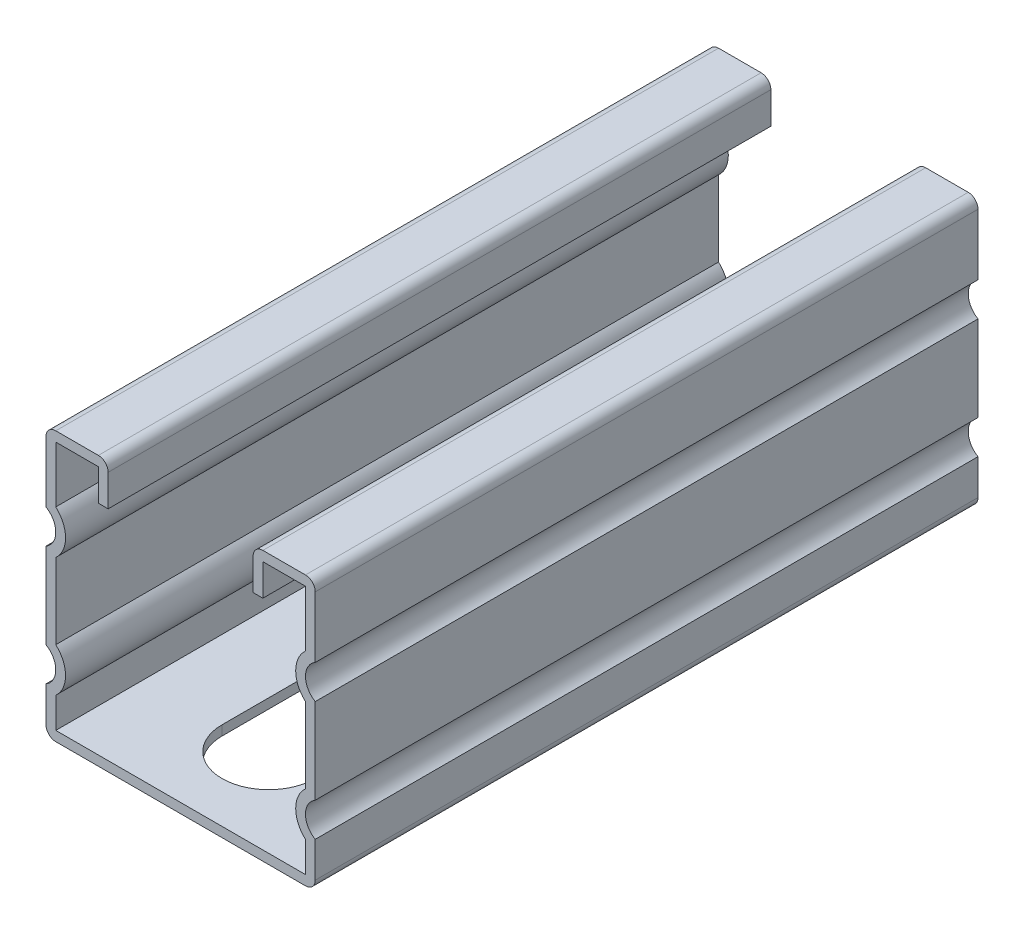
SolidWorks part; units mm, degrees
ref_plane "Plane1" through (0, 0, 0) normal (0, 0, 1) x (1, 0, 0)
ref_plane "Plane2" through (0, 0, 0) normal (0, 1, 0) x (1, 0, 0)
ref_plane "Plane3" through (0, 0, 0) normal (1, 0, 0) x (0, 0, -1)
sketch "Sketch1" plane through (0, 0, 0) normal (0, 0, 1) x (1, 0, 0)
  line L0 (-20.6375, 21.1074) -> (-20.6375, 11.7397)
  line L1 (-20.6375, 6.5483) -> (-20.6375, -6.5483)
  line L2 (-19.1389, -18.669) -> (19.1389, -18.669)
  line L3 (20.6375, -17.1704) -> (20.6375, -11.7397)
  line L4 (20.6375, 11.7397) -> (20.6375, 21.1074)
  line L5 (19.1389, 22.606) -> (12.6111, 22.606)
  line L6 (11.1125, 21.1074) -> (11.1125, 16.256)
  line L7 (-19.1389, 22.606) -> (-12.6111, 22.606)
  line L8 (-11.1125, 21.1074) -> (-11.1125, 16.256)
  line L9 (19.1389, -12.495) -> (19.1389, 12.495) construction
  line L10 (-19.1389, 12.495) -> (-19.1389, -12.495) construction
  line L11 (-12.6111, 21.1074) -> (-12.6111, 16.256)
  line L12 (-19.1389, 21.1074) -> (-12.6111, 21.1074)
  line L13 (-19.1389, 21.1074) -> (-19.1389, 12.495)
  line L14 (-19.1389, 5.793) -> (-19.1389, -5.793)
  line L15 (-19.1389, -17.1704) -> (19.1389, -17.1704)
  line L16 (19.1389, -17.1704) -> (19.1389, -12.495)
  line L17 (19.1389, 12.495) -> (19.1389, 21.1074)
  line L18 (19.1389, 21.1074) -> (12.6111, 21.1074)
  line L19 (12.6111, 21.1074) -> (12.6111, 16.256)
  line L20 (-12.6111, 16.256) -> (-11.1125, 16.256)
  line L21 (11.1125, 16.256) -> (12.6111, 16.256)
  line L22 (-10.16, 0) -> (12.7, 0) construction
  line L23 (-20.6375, -11.7397) -> (-20.6375, -17.1704)
  line L24 (-19.1389, -12.495) -> (-19.1389, -17.1704)
  line L25 (20.6375, -6.5483) -> (20.6375, 6.5483)
  line L26 (19.1389, -5.793) -> (19.1389, 5.793)
  arc A0 (20.6375, 11.7397) -> (20.6375, 6.5483) centre (22.1361, 9.144) ccw
  arc A1 (-20.6375, 6.5483) -> (-20.6375, 11.7397) centre (-22.1361, 9.144) ccw
  arc A2 (-12.6111, 22.606) -> (-11.1125, 21.1074) centre (-12.6111, 21.1074) cw
  arc A3 (-20.6375, 21.1074) -> (-19.1389, 22.606) centre (-19.1389, 21.1074) cw
  arc A4 (-19.1389, -18.669) -> (-20.6375, -17.1704) centre (-19.1389, -17.1704) cw
  arc A5 (20.6375, -17.1704) -> (19.1389, -18.669) centre (19.1389, -17.1704) cw
  arc A6 (19.1389, 22.606) -> (20.6375, 21.1074) centre (19.1389, 21.1074) cw
  arc A7 (11.1125, 21.1074) -> (12.6111, 22.606) centre (12.6111, 21.1074) cw
  arc A8 (-19.1389, 5.793) -> (-19.1389, 12.495) centre (-22.1361, 9.144) ccw
  arc A9 (19.1389, 12.495) -> (19.1389, 5.793) centre (22.1361, 9.144) ccw
  arc A10 (20.6375, -11.7397) -> (20.6375, -6.5483) centre (22.1361, -9.144) cw
  arc A11 (19.1389, -12.495) -> (19.1389, -5.793) centre (22.1361, -9.144) cw
  arc A12 (-19.1389, -5.793) -> (-19.1389, -12.495) centre (-22.1361, -9.144) cw
  arc A13 (-20.6375, -6.5483) -> (-20.6375, -11.7397) centre (-22.1361, -9.144) cw
  dimension "D9" = 2.9972
  dimension "D10" = 2.9972
  dimension "D1" = 20.6375
  dimension "Width" = 41.275
  dimension "base" = 18.669
  dimension "ToeHt" = 22.606
  dimension "D6" = 22.225
  dimension "edge" = 9.525
  dimension "Lip" = 6.35
  dimension "D2" = 9.525
  dimension "gauge" = 1.4986
extrude "Base-Extrude" add sketch "Sketch1" along normal blind 101.6
extrude "Slot" cut sketch "Sketch2" against normal through all
sketch "Sketch2" plane through (1.1214, -18.669, -18.7802) normal (0, -1, 0) x (1, 0, 0)
  line L0 (6.0223, 56.0864) -> (6.0223, 41.7989)
  line L1 (-8.2652, 41.7989) -> (-8.2652, 56.0864)
  arc A0 (-8.2652, 41.7989) -> (6.0223, 41.7989) centre (-1.1214, 41.7989) ccw
  arc A1 (6.0223, 56.0864) -> (-8.2652, 56.0864) centre (-1.1214, 56.0864) ccw
  dimension "D3" = 14.2875
  dimension "D1" = 23.0188
  dimension "D2" = 14.2875
pattern_linear "LPattern1" count 2 spacing 50.8 along (0, 0, 1) of "Slot"
equation "\"D1@Sketch1\" = \"Width@Sketch1\" / 2"
equation "\"D6@Sketch1\" = \"Width@Sketch1\" - 2 * \"edge@Sketch1\""
equation "\"D10@Sketch1\" = 2 * \"gauge@Sketch1\""
equation "\"D9@Sketch1\" = \"D10@Sketch1\""
equation "\"D2@Sketch1\" = \"edge@Sketch1\""
equation "\"D1@LPattern1\" = \"D1@Base-Extrude\" / \"D3@LPattern1\""
